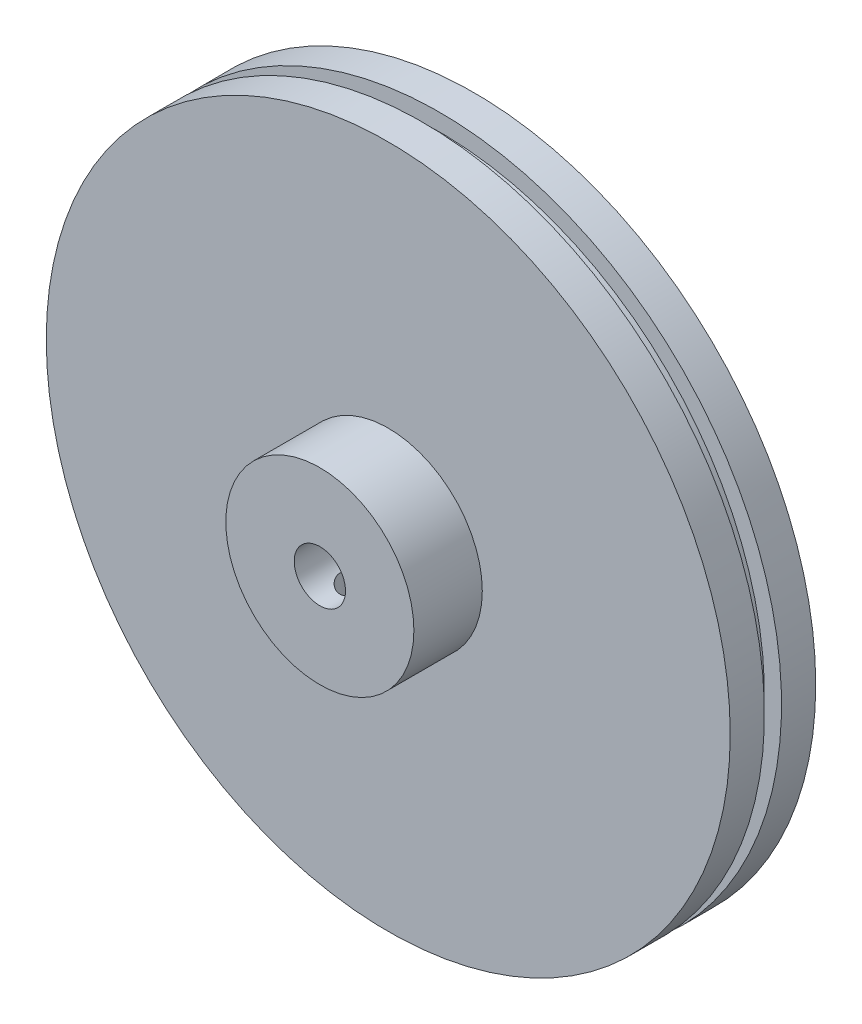
SolidWorks part; units mm, degrees
material "黄銅"
ref_plane "正面" through (0, 0, 0) normal (0, 0, 1) x (1, 0, 0)
ref_plane "平面" through (0, 0, 0) normal (0, 1, 0) x (1, 0, 0)
ref_plane "右側面" through (0, 0, 0) normal (1, 0, 0) x (0, 0, -1)
sketch "ｽｹｯﾁ1" plane through (0, 0, 0) normal (0, 0, 1) x (1, 0, 0)
  circle A0 centre (0, 0) radius 40
  dimension "D1" = 80
extrude "ﾎﾞｽ - 押し出し1" add sketch "ｽｹｯﾁ1" along normal blind 10
sketch "ｽｹｯﾁ2" plane through (0, 0, 10) normal (0, 0, 1) x (1, 0, 0)
  circle A0 centre (0, 0) radius 11
  dimension "D1" = 22
extrude "ﾎﾞｽ - 押し出し2" add sketch "ｽｹｯﾁ2" along normal blind 8
sketch "ｽｹｯﾁ3" plane through (0, 0, 18) normal (0, 0, 1) x (1, 0, 0)
  circle A0 centre (0, 0) radius 3
  dimension "D1" = 6
extrude "ｶｯﾄ - 押し出し1" cut sketch "ｽｹｯﾁ3" against normal through all
hole_wizard "M4x0.7 ねじ穴1" positions "3Dｽｹｯﾁ1" profile "ｽｹｯﾁ4" tap size "M4x0.7" standard "JIS"
sketch3d "3Dｽｹｯﾁ1"
  point P0 (0, -11, 14)
  dimension "D1" = 4
sketch "ｽｹｯﾁ4" plane through (0, -11, 14) normal (1, 0, 0) x (0, 0, -1)
  line L0 (0, 0) -> (0, 8)
  line L1 (0, 8) -> (1.65, 8)
  line L2 (1.65, 8) -> (1.65, 0)
  line L5 (1.65, 0) -> (0, 0)
  line L11 (0, -6.35) -> (0, 107.95) construction
  dimension "次ｻｰﾌｪｽまでのねじ下穴ﾄﾞﾘﾙ直径" = 3.3
  dimension "次ｻｰﾌｪｽまでのねじ下穴ﾄﾞﾘﾙの深さ" = 8
cosmetic thread "穴のねじ山1" parameters "D2"=4
ref_plane "平面1" through (0, 0, 5) normal (0, 0, -1) x (-1, 0, 0)
sketch "ｽｹｯﾁ5" plane through (0, 0, 5) normal (0, 0, -1) x (-1, 0, 0)
  circle A0 centre (0, 0) radius 38
  dimension "D1" = 76
extrude "ｶｯﾄ - 押し出し2" cut sketch "ｽｹｯﾁ5" against normal blind 1 and the other way blind 1 flip side to cut contours A0
